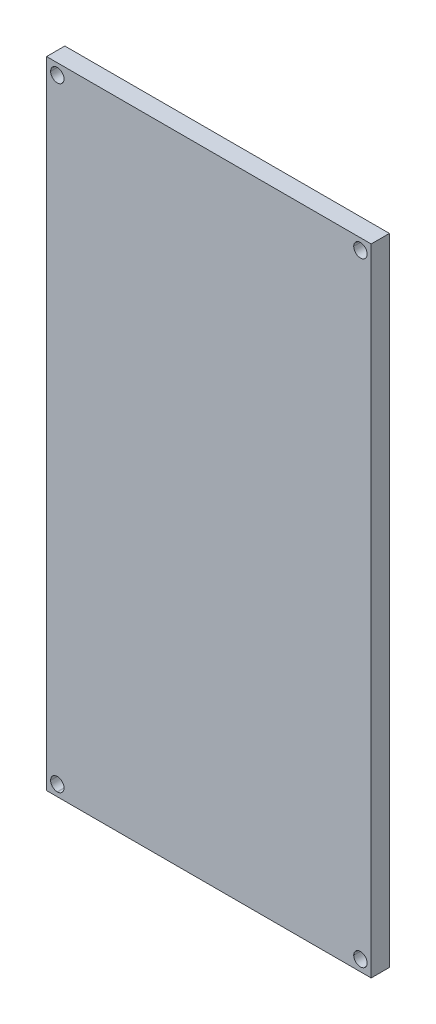
SolidWorks part; units mm, degrees
ref_plane "Front Plane" through (0, 0, 0) normal (0, 0, 1) x (1, 0, 0)
ref_plane "Top Plane" through (0, 0, 0) normal (0, 1, 0) x (1, 0, 0)
ref_plane "Right Plane" through (0, 0, 0) normal (1, 0, 0) x (0, 0, -1)
sketch "Model" plane through (0, 0, 0) normal (0, 0, 1) x (1, 0, 0)
  line L0 (1338.9357, -390.0908) -> (1258.9357, -390.0908)
  line L1 (1258.9357, -390.0908) -> (1258.9357, -233.413)
  line L2 (1258.9357, -233.413) -> (1338.9357, -233.413)
  line L3 (1338.9357, -233.413) -> (1338.9357, -390.0908)
  spline S0 degree 3 poles (1334.6355, -236.0629) (1334.6355, -235.1517) (1335.3741, -234.4131) (1336.2857, -234.4131) (1337.1966, -234.4131) (1337.9355, -235.1517) (1337.9355, -236.0629) knots 2 2 2 2 3 3 3 4 4 4 4
  spline S1 degree 3 poles (1337.9355, -236.0629) (1337.9355, -236.9742) (1337.1966, -237.7131) (1336.2857, -237.7131) (1335.3741, -237.7131) (1334.6355, -236.9742) (1334.6355, -236.0629) knots 0 0 0 0 1 1 1 2 2 2 2
  spline S2 degree 3 poles (1259.9355, -236.0629) (1259.9355, -235.1517) (1260.6741, -234.4131) (1261.5857, -234.4131) (1262.4966, -234.4131) (1263.2356, -235.1517) (1263.2356, -236.0629) knots 2 2 2 2 3 3 3 4 4 4 4
  spline S3 degree 3 poles (1263.2356, -236.0629) (1263.2356, -236.9742) (1262.4966, -237.7131) (1261.5857, -237.7131) (1260.6741, -237.7131) (1259.9355, -236.9742) (1259.9355, -236.0629) knots 0 0 0 0 1 1 1 2 2 2 2
  spline S4 degree 3 poles (1259.9355, -387.3929) (1259.9355, -386.4817) (1260.6741, -385.743) (1261.5857, -385.743) (1262.4966, -385.743) (1263.2359, -386.4817) (1263.2359, -387.3929) knots 2 2 2 2 3 3 3 4 4 4 4
  spline S5 degree 3 poles (1263.2359, -387.3929) (1263.2359, -388.3041) (1262.4966, -389.0431) (1261.5857, -389.0431) (1260.6741, -389.0431) (1259.9355, -388.3041) (1259.9355, -387.3929) knots 0 0 0 0 1 1 1 2 2 2 2
  spline S6 degree 3 poles (1334.6355, -387.3929) (1334.6355, -386.4817) (1335.3741, -385.743) (1336.2857, -385.743) (1337.1966, -385.743) (1337.9359, -386.4817) (1337.9359, -387.3929) knots 2 2 2 2 3 3 3 4 4 4 4
  spline S7 degree 3 poles (1337.9359, -387.3929) (1337.9359, -388.3041) (1337.1966, -389.0431) (1336.2857, -389.0431) (1335.3741, -389.0431) (1334.6355, -388.3041) (1334.6355, -387.3929) knots 0 0 0 0 1 1 1 2 2 2 2
extrude "Boss-Extrude1" add sketch "Model" along normal blind 4.5
sketch "Sketch2" plane through (0, 0, 4.5) normal (0, 0, 1) x (1, 0, 0)
  circle A0 centre (1336.2855, -236.0955) radius 1.6503
  circle A2 centre (1261.5857, -387.3929) radius 1.6502
extrude "Cut-Extrude1" cut sketch "Sketch2" against normal blind 10
